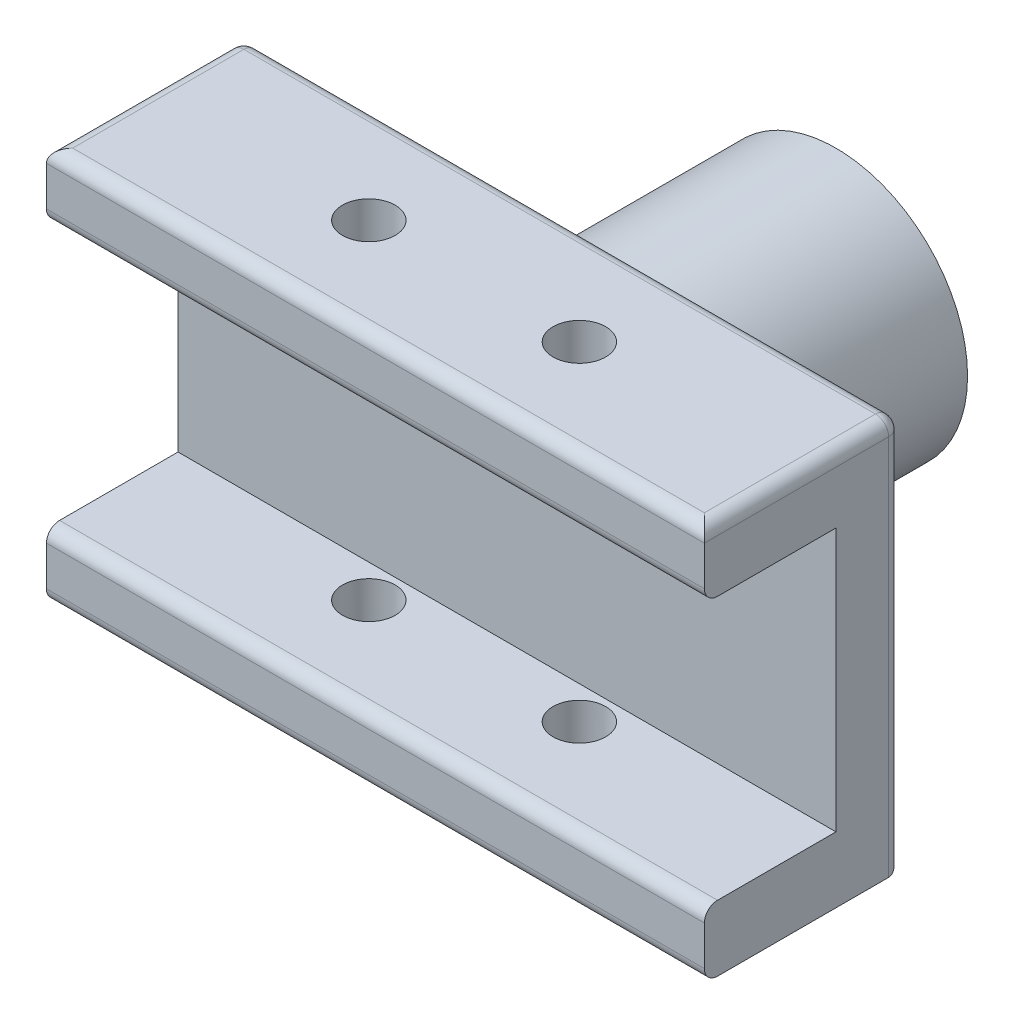
SolidWorks part; units mm, degrees
ref_plane "Front Plane" through (0, 0, 0) normal (0, 0, 1) x (1, 0, 0)
ref_plane "Top Plane" through (0, 0, 0) normal (0, 1, 0) x (1, 0, 0)
ref_plane "Right Plane" through (0, 0, 0) normal (1, 0, 0) x (0, 0, -1)
sketch "Sketch1" plane through (0, 0, 0) normal (0, 0, 1) x (1, 0, 0)
  line L1 (-25, 15) -> (25, 15)
  line L2 (-25, 15) -> (-25, -15)
  line L3 (-25, -15) -> (25, -15)
  line L4 (25, 15) -> (25, -15)
  line L5 (-25, 15) -> (25, -15) construction
  line L6 (-25, -15) -> (25, 15) construction
  point P0 (0, 0)
  dimension "D1" = 30
  dimension "D2" = 50
extrude "Boss-Extrude1" add sketch "Sketch1" along normal blind 15
sketch "Sketch2" plane through (0, 0, 15) normal (0, 0, 1) x (1, 0, 0)
  line L0 (25, -15) -> (25, 15) construction
  line L1 (-25, 10) -> (25, 10)
  line L2 (-25, 10) -> (-25, -10)
  line L3 (-25, -10) -> (25, -10)
  line L4 (25, 10) -> (25, -10)
  line L5 (-25, 10) -> (25, -10) construction
  line L6 (-25, -10) -> (25, 10) construction
  line L7 (25, 15) -> (-25, 15) construction
  point P0 (0, 0)
  dimension "D1" = 5
extrude "Cut-Extrude1" cut sketch "Sketch2" against normal blind 10
sketch "Sketch3" plane through (0, 15, 0) normal (0, 1, 0) x (1, 0, 0)
  line L0 (0, -15) -> (0, -7.5) construction
  line L1 (25, -15) -> (-25, -15) construction
  line L2 (-8, -7.5) -> (8, -7.5) construction
  circle A0 centre (-8, -7.5) radius 2
  circle A1 centre (8, -7.5) radius 2
  dimension "D1" = 4
  dimension "D2" = 16
  dimension "D3" = 7.5
extrude "Cut-Extrude2" cut sketch "Sketch3" against normal through all
sketch "Sketch4" plane through (0, 0, 0) normal (0, 0, -1) x (-1, 0, 0)
  circle A0 centre (0, 0) radius 10
  dimension "D1" = 20
extrude "Boss-Extrude2" add sketch "Sketch4" along normal blind 20
sketch "Sketch5" plane through (0, 0, -20) normal (0, 0, -1) x (-1, 0, 0)
  circle A0 centre (0, 0) radius 7.5
  dimension "D1" = 15
fillet "Fillet3" radius 1 1 edges at (0, -10, 15)
fillet "Fillet4" radius 1 1 edges at (0, -15, 15)
fillet "Fillet5" radius 1 7 edges at (25, 0, 0) (0, 15, 0) (-25, 0, 0) (0, -15, 0) (-25, 15, 7.5) (25, 15, 7.5) (0, 15, 15)
fillet "Fillet6" radius 1 1 edges at (0, 10, 15)
fillet "Fillet7" radius 1 1 edges at (-10, 0, 0)
